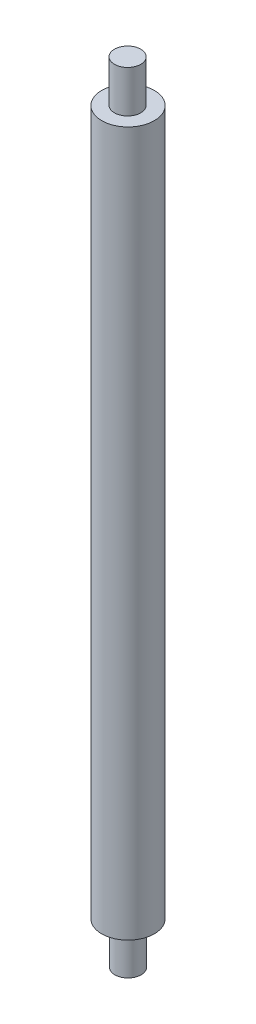
SolidWorks part; units mm, degrees
ref_plane "Front Plane" through (0, 0, 0) normal (0, 0, 1) x (1, 0, 0)
ref_plane "Top Plane" through (0, 0, 0) normal (0, 1, 0) x (1, 0, 0)
ref_plane "Right Plane" through (0, 0, 0) normal (1, 0, 0) x (0, 0, -1)
sketch "Sketch1" plane through (0, 0, 0) normal (0, 1, 0) x (1, 0, 0)
  circle A0 centre (0, 0) radius 6.35
  dimension "D1" = 12.7
extrude "Boss-Extrude1" add sketch "Sketch1" along normal blind 190.5
sketch "Sketch2" plane through (0, 190.5, 0) normal (0, 1, 0) x (1, 0, 0)
  circle A0 centre (0, 0) radius 6.35
  circle A1 centre (-0.0991, 0) radius 3.175
  dimension "D1" = 6.35
extrude "Cut-Extrude1" cut sketch "Sketch2" against normal blind 10.16
sketch "Sketch3" plane through (0, 0, 0) normal (0, -1, 0) x (1, 0, 0)
  circle A0 centre (0, 0) radius 6.35
  circle A1 centre (0, 0) radius 3.175
  dimension "D1" = 6.35
extrude "Cut-Extrude2" cut sketch "Sketch3" against normal blind 10.16
